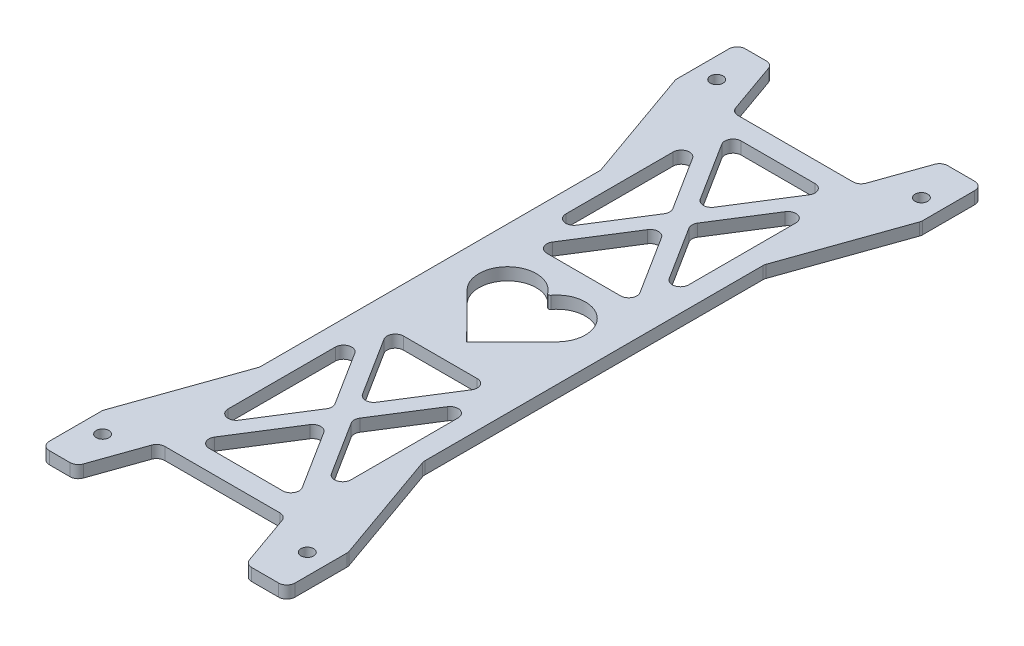
SolidWorks part; units mm, degrees
material "环氧树脂板"
ref_plane "前视基准面" through (0, 0, 0) normal (0, 0, 1) x (1, 0, 0)
ref_plane "上视基准面" through (0, 0, 0) normal (0, 1, 0) x (1, 0, 0)
ref_plane "右视基准面" through (0, 0, 0) normal (1, 0, 0) x (0, 0, -1)
sketch "草图1" plane through (0, 0, 0) normal (0, 1, 0) x (1, 0, 0)
  line L0 (-30, 75) -> (30, 75) construction
  line L1 (30, -85) -> (20, -85)
  line L2 (30, -85) -> (30, -69.9769)
  line L3 (30, 85) -> (20, 85)
  line L4 (-30, -85) -> (-30, -69.9769)
  line L5 (30, -85) -> (-30, 85) construction
  line L6 (30, 85) -> (-30, -85) construction
  line L7 (-21.5163, 85) -> (-16.2222, 70)
  line L8 (-16.2222, 70) -> (14.7059, 70)
  line L9 (14.7059, 70) -> (20, 85)
  line L10 (-30, 69.9769) -> (-20, 41.6435)
  line L11 (-20, 41.6435) -> (-20, -41.6435)
  line L12 (-20, -41.6435) -> (-30, -69.9769)
  line L13 (0, 0) -> (-30, 0) construction
  line L14 (0, 0) -> (0, 36.1537) construction
  line L15 (20, -41.6435) -> (30, -69.9769)
  line L16 (20, 41.6435) -> (20, -41.6435)
  line L17 (30, 69.9769) -> (20, 41.6435)
  line L18 (-30, 69.9769) -> (-30, 85)
  line L19 (30, 69.9769) -> (30, 85)
  line L20 (-21.5163, -85) -> (-16.2222, -70)
  line L21 (-16.2222, -70) -> (14.7059, -70)
  line L22 (14.7059, -70) -> (20, -85)
  line L23 (-21.5163, 85) -> (-30, 85)
  line L24 (-21.5163, -85) -> (-30, -85)
  line L25 (-10.9723, 0) -> (0, -11.0729)
  line L26 (0, -11.0729) -> (10.9723, 0)
  line L28 (15, 17.5) -> (-15, 17.5) construction
  line L29 (15, 17.5) -> (15, 65) construction
  line L30 (15, 65) -> (-15, 65) construction
  line L31 (-15, 17.5) -> (-15, 65) construction
  line L32 (15, 17.5) -> (-15, 65) construction
  line L33 (15, 65) -> (-15, 17.5) construction
  line L41 (12.6345, 65) -> (0, 44.9954)
  line L42 (-12.6345, 17.5) -> (0, 37.5046)
  line L43 (-12.6345, 65) -> (0, 44.9954)
  line L44 (-15, 61.2546) -> (-2.3655, 41.25)
  line L45 (-12.6345, 65) -> (12.6345, 65)
  line L46 (15, 61.2546) -> (15, 21.2454)
  line L47 (12.6345, 17.5) -> (-12.6345, 17.5)
  line L48 (-15, 21.2454) -> (-15, 61.2546)
  line L49 (2.3655, 41.25) -> (15, 21.2454)
  line L50 (-2.3655, 41.25) -> (-15, 21.2454)
  line L51 (0, 37.5046) -> (12.6345, 17.5)
  line L52 (2.3655, 41.25) -> (15, 61.2546)
  line L53 (2.3655, -41.25) -> (15, -61.2546)
  line L54 (2.3655, -41.25) -> (15, -21.2454)
  line L55 (15, -61.2546) -> (15, -21.2454)
  line L56 (-12.6345, -65) -> (12.6345, -65)
  line L57 (-12.6345, -65) -> (0, -44.9954)
  line L58 (12.6345, -65) -> (0, -44.9954)
  line L59 (-15, -21.2454) -> (-15, -61.2546)
  line L60 (-2.3655, -41.25) -> (-15, -21.2454)
  line L61 (-15, -61.2546) -> (-2.3655, -41.25)
  line L62 (12.6345, -17.5) -> (-12.6345, -17.5)
  line L63 (0, -37.5046) -> (12.6345, -17.5)
  line L64 (-12.6345, -17.5) -> (0, -37.5046)
  circle A0 centre (-25, 75) radius 1.55
  circle A1 centre (25, 75) radius 1.55
  circle A2 centre (25, -75) radius 1.55
  circle A3 centre (-25, -75) radius 1.55
  arc A4 (0, 8.5327) -> (-10.9723, 0) centre (-6, 4.9271) ccw
  arc A5 (10.9723, 0) -> (0, 8.5327) centre (6, 4.9271) ccw
  point P0 (0, 0)
  point P38 (0, 41.25)
  dimension "D3" = 3.1
  dimension "D12" = 14
  dimension "D1" = 170
  dimension "D2" = 60
  dimension "D4" = 5
  dimension "D5" = 5
  dimension "D6" = 10
  dimension "D7" = 8
  dimension "D8" = 10
  dimension "D9" = 5
  dimension "D10" = 5
  dimension "D11" = 40
  dimension "D13" = 12
  dimension "D14" = 16
  dimension "D15" = 17.5
  dimension "D16" = 5
  dimension "D17" = 5
  dimension "D19" = 4
extrude "凸台-拉伸1" add sketch "草图1" along normal blind 3
fillet "圆角1" radius 2 44 edges at (12.6345, 1.5, 17.5) (0, 1.5, 37.5046) (-12.6345, 1.5, 65) (12.6345, 1.5, 65) (0, 1.5, 44.9954) (-2.3655, 1.5, -41.25) (-15, 1.5, -61.2546) (-15, 1.5, -21.2454) (2.3655, 1.5, -41.25) (15, 1.5, -21.2454) (15, 1.5, -61.2546) (2.3655, 1.5, 41.25) (15, 1.5, 61.2546) (15, 1.5, 21.2454) (0, 1.5, -44.9954) (12.6345, 1.5, -65) (-12.6345, 1.5, -65) (12.6345, 1.5, -17.5) (0, 1.5, -37.5046) (-12.6345, 1.5, -17.5) (-12.6345, 1.5, 17.5) (-15, 1.5, 61.2546) (-2.3655, 1.5, 41.25) (-15, 1.5, 21.2454) (-21.5163, 1.5, -85) (-16.2222, 1.5, -70) (14.7059, 1.5, -70) (20, 1.5, -85) (30, 1.5, -85) (30, 1.5, -69.9769) (20, 1.5, -41.6435) (20, 1.5, 41.6435) (30, 1.5, 69.9769) (30, 1.5, 85) (20, 1.5, 85) (14.7059, 1.5, 70) (-16.2222, 1.5, 70) (-21.5163, 1.5, 85) (-30, 1.5, 69.9769) (-20, 1.5, 41.6435) (-20, 1.5, -41.6435) (-30, 1.5, -69.9769) (-30, 1.5, -85) (-30, 1.5, 85)
fillet "圆角2" radius 0.5 1 edges at (0, 1.5, -8.5327)
